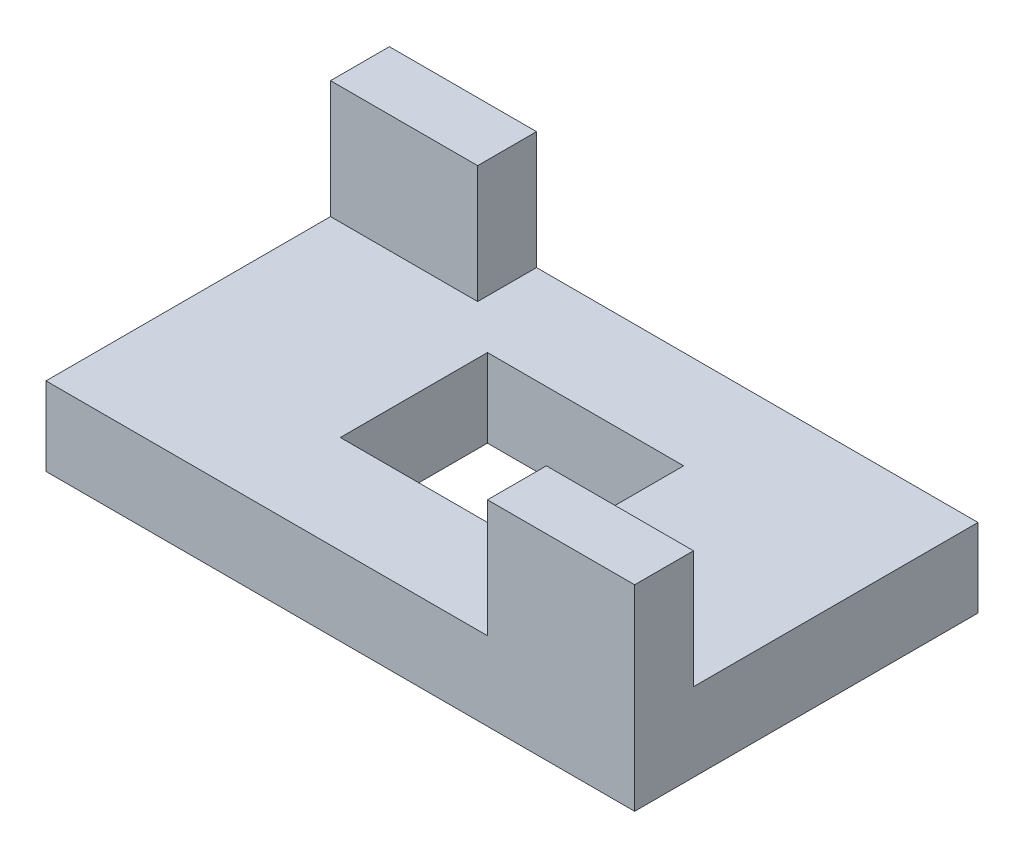
SolidWorks part; units mm, degrees
material "Alloy Steel (SS)"
ref_plane "Front Plane" through (0, 0, 0) normal (0, 0, 1) x (1, 0, 0)
ref_plane "Top Plane" through (0, 0, 0) normal (0, 1, 0) x (1, 0, 0)
ref_plane "Right Plane" through (0, 0, 0) normal (1, 0, 0) x (0, 0, -1)
sketch "Sketch1" plane through (0, 0, 0) normal (0, 1, 0) x (1, 0, 0)
  line L1 (-30, 17.5) -> (30, 17.5)
  line L2 (-30, 17.5) -> (-30, -17.5)
  line L3 (-30, -17.5) -> (30, -17.5)
  line L4 (30, 17.5) -> (30, -17.5)
  line L5 (-30, 17.5) -> (30, -17.5) construction
  line L6 (-30, -17.5) -> (30, 17.5) construction
  point P0 (0, 0)
  dimension "D1" = 60
  dimension "D2" = 35
  dimension "D3" = 30
  dimension "D4" = 17.5
extrude "Boss-Extrude1" add sketch "Sketch1" along normal blind 8 contours L2 L1 L4 L3
sketch "Sketch2" plane through (0, 0, 0) normal (0, 1, 0) x (1, 0, 0)
  line L1 (-30, 17.5) -> (-15, 17.5)
  line L2 (-30, 17.5) -> (-30, 11.5)
  line L3 (-30, 11.5) -> (-15, 11.5)
  line L4 (-15, 17.5) -> (-15, 11.5)
  line L5 (30, -17.5) -> (15, -17.5)
  line L6 (30, -17.5) -> (30, -11.5)
  line L7 (30, -11.5) -> (15, -11.5)
  line L8 (15, -17.5) -> (15, -11.5)
  dimension "D1" = 6
  dimension "D2" = 15
  dimension "D3" = 15
  dimension "D4" = 6
extrude "Boss-Extrude2" add sketch "Sketch2" along normal blind 20
sketch "Sketch3" plane through (0, 0, 0) normal (0, 1, 0) x (1, 0, 0)
  line L0 (-30, 11.5) -> (-30, -17.5) construction
  line L1 (-10, 7.5) -> (10, 7.5)
  line L2 (-10, 7.5) -> (-10, -7.5)
  line L3 (-10, -7.5) -> (10, -7.5)
  line L4 (10, 7.5) -> (10, -7.5)
  line L5 (-10, 7.5) -> (10, -7.5) construction
  line L6 (-10, -7.5) -> (10, 7.5) construction
  line L8 (-30, -17.5) -> (15, -17.5) construction
  point P0 (0, 0)
  dimension "D1" = 20
  dimension "D3" = 10
extrude "Cut-Extrude2" cut sketch "Sketch3" along normal through all
